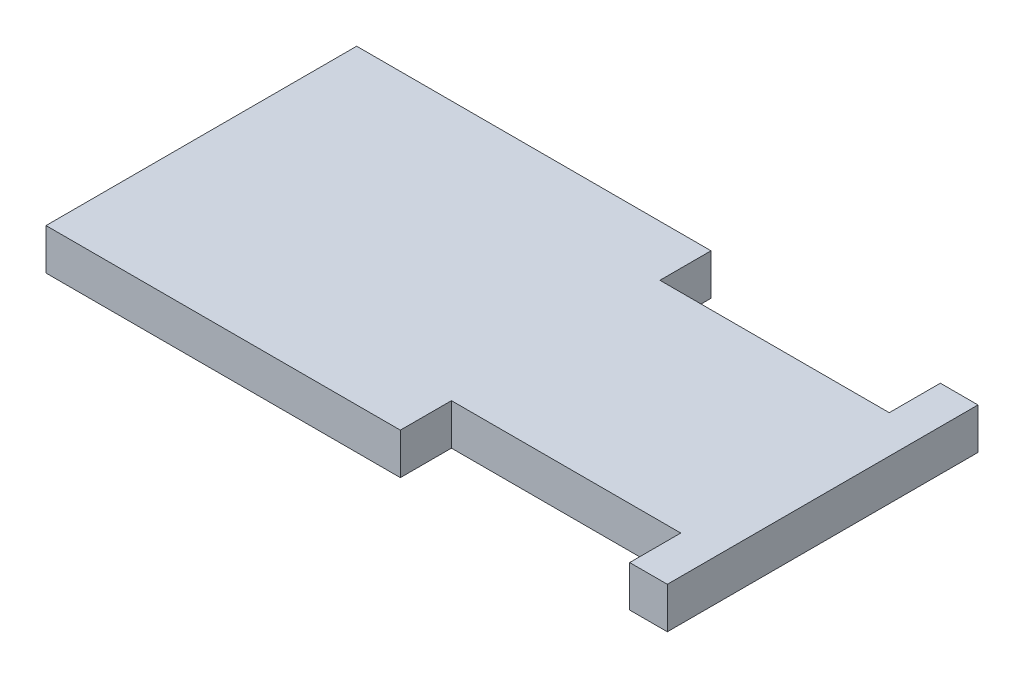
SolidWorks part; units mm, degrees
ref_plane "Front Plane" through (0, 0, 0) normal (0, 0, 1) x (1, 0, 0)
ref_plane "Top Plane" through (0, 0, 0) normal (0, 1, 0) x (1, 0, 0)
ref_plane "Right Plane" through (0, 0, 0) normal (1, 0, 0) x (0, 0, -1)
sketch "Sketch1" plane through (0, 0, 0) normal (0, 1, 0) x (1, 0, 0)
  line L1 (-101.6, -50.8) -> (101.6, -50.8)
  line L2 (-101.6, -50.8) -> (-101.6, 50.8)
  line L3 (-101.6, 50.8) -> (101.6, 50.8)
  line L4 (101.6, -50.8) -> (101.6, 50.8)
  line L5 (-101.6, -50.8) -> (101.6, 50.8) construction
  line L6 (-101.6, 50.8) -> (101.6, -50.8) construction
  point P0 (0, 0)
extrude "Boss-Extrude2" add sketch "Sketch1" along normal blind 13.462
sketch "Sketch4" plane through (0, 13.462, 0) normal (0, 1, 0) x (1, 0, 0)
  line L0 (-7.4041, 0) -> (7.4041, 0) construction
  line L1 (14.2855, -34.0904) -> (89.2855, -34.0904)
  line L2 (14.2855, -34.0904) -> (14.2855, -57.4666)
  line L3 (14.2855, -57.4666) -> (89.2855, -57.4666)
  line L4 (89.2855, -34.0904) -> (89.2855, -57.4666)
  line L5 (14.2855, 57.4666) -> (89.2855, 57.4666)
  line L6 (89.2855, 34.0904) -> (89.2855, 57.4666)
  line L7 (14.2855, 34.0904) -> (89.2855, 34.0904)
  line L8 (14.2855, 34.0904) -> (14.2855, 57.4666)
extrude "Cut-Extrude1" cut sketch "Sketch4" against normal blind 28.448 and the other way blind 13.208
sketch "Sketch5" plane through (0, 0, 0) normal (0, -1, 0) x (-1, 0, 0)
  line L0 (7.6699, -60.641) -> (7.6699, -52.7262)
  circle A0 centre (81.6514, 0) radius 16.1794
extrude "Boss-Extrude4" add sketch "Sketch5" along normal blind 1.524 contours A0
sketch "Sketch6" plane through (0, -1.524, 0) normal (0, -1, 0) x (1, 0, 0)
  circle A0 centre (-81.6514, 0) radius 8.0536
extrude "Boss-Extrude6" add sketch "Sketch6" along normal blind 11.43 contours A0
sketch "Sketch7" plane through (0, -12.954, 0) normal (0, -1, 0) x (1, 0, 0)
  line L0 (-86.4868, 0) -> (-76.816, 0)
  arc A0 (-76.816, 0) -> (-86.4868, 0) centre (-81.6514, 0) ccw
revolve "Revolve1" add sketch "Sketch7" angle 360 about L0
